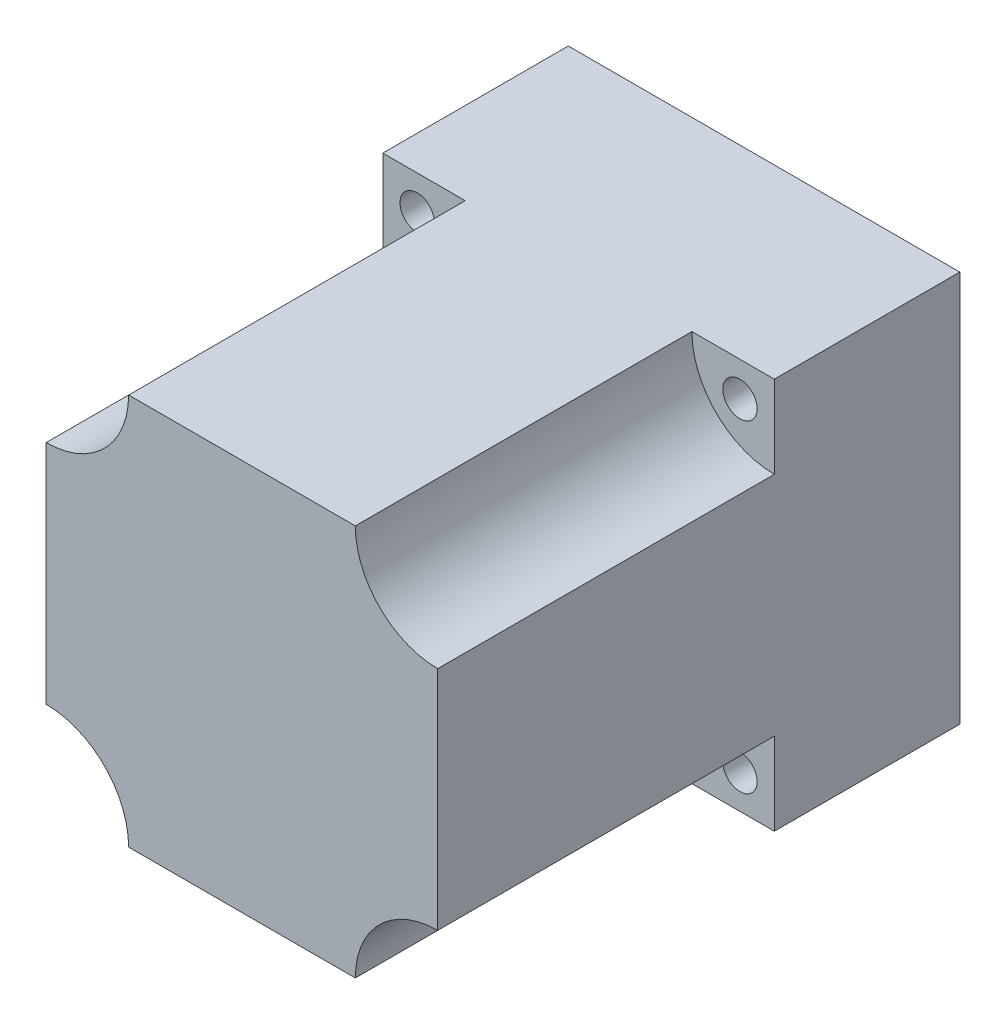
SolidWorks part; units mm, degrees
material "0.7060 (EN-GJS-600-3)"
ref_plane "前视基准面" through (0, 0, 0) normal (0, 0, 1) x (1, 0, 0)
ref_plane "上视基准面" through (0, 0, 0) normal (0, 1, 0) x (1, 0, 0)
ref_plane "右视基准面" through (0, 0, 0) normal (1, 0, 0) x (0, 0, -1)
other "Configuration Table"
sketch "草图1" plane through (0, 0, 0) normal (0, 0, 1) x (1, 0, 0)
  line L1 (-28.5, 28.5) -> (28.5, 28.5)
  line L2 (-28.5, 28.5) -> (-28.5, -28.5)
  line L3 (-28.5, -28.5) -> (28.5, -28.5)
  line L4 (28.5, 28.5) -> (28.5, -28.5)
  line L5 (-28.5, 28.5) -> (28.5, -28.5) construction
  line L6 (-28.5, -28.5) -> (28.5, 28.5) construction
  point P0 (0, 0)
  dimension "D1" = 57
  dimension "D2" = 57
extrude "凸台-拉伸1" add sketch "草图1" along normal blind 76
sketch "草图2" plane through (0, 0, 76) normal (0, 0, 1) x (1, 0, 0)
  circle A0 centre (-28.5, 28.5) radius 12
  circle A1 centre (28.5, 28.5) radius 12
  circle A2 centre (-28.5, -28.5) radius 12
  circle A3 centre (28.5, -28.5) radius 12
extrude "切除-拉伸1" cut sketch "草图2" against normal blind 49
sketch "草图3" plane through (0, 0, 0) normal (0, 0, -1) x (-1, 0, 0)
  line L0 (-23.5, 23.5) -> (23.5, 23.5) construction
  line L1 (23.5, 23.5) -> (23.5, -23.5) construction
  line L2 (23.5, -23.5) -> (-23.5, -23.5) construction
  line L3 (-23.5, -23.5) -> (-23.5, 23.5) construction
  line L4 (-28.5, 28.5) -> (28.5, 28.5) construction
  line L5 (-28.5, -28.5) -> (-28.5, 28.5) construction
  circle A0 centre (-23.5, 23.5) radius 2.5
  circle A1 centre (23.5, 23.5) radius 2.5
  circle A2 centre (-23.5, -23.5) radius 2.5
  circle A3 centre (23.5, -23.5) radius 2.5
  dimension "D1" = 47
  dimension "D5" = 5
  dimension "D2" = 47
  dimension "D3" = 5
  dimension "D4" = 5
extrude "切除-拉伸2" cut sketch "草图3" against normal through all
sketch "草图4" plane through (0, 0, 0) normal (0, 0, -1) x (-1, 0, 0)
  circle A0 centre (0, 0) radius 19
extrude "凸台-拉伸2" add sketch "草图4" along normal blind 1.6
sketch "草图5" plane through (0, 0, -1.6) normal (0, 0, -1) x (-1, 0, 0)
  circle A0 centre (0, 0) radius 4
extrude "凸台-拉伸3" add sketch "草图5" along normal blind 18.4
sketch "草图6" plane through (0, 0, -20) normal (0, 0, -1) x (-1, 0, 0)
  line L0 (-6.5173, 4.5) -> (-6.5173, 3.5)
  line L1 (-6.5173, 4.5) -> (6.5173, 4.5)
  line L2 (-6.5173, 3.5) -> (6.5173, 3.5)
  line L3 (6.5173, 4.5) -> (6.5173, 3.5)
  line L4 (-6.5173, 4.5) -> (6.5173, 3.5) construction
  line L5 (-6.5173, 3.5) -> (6.5173, 4.5) construction
  point P1 (0, 4)
  point P2 (0, 4)
  dimension "D1" = 1
extrude "切除-拉伸3" cut sketch "草图6" against normal blind 15
